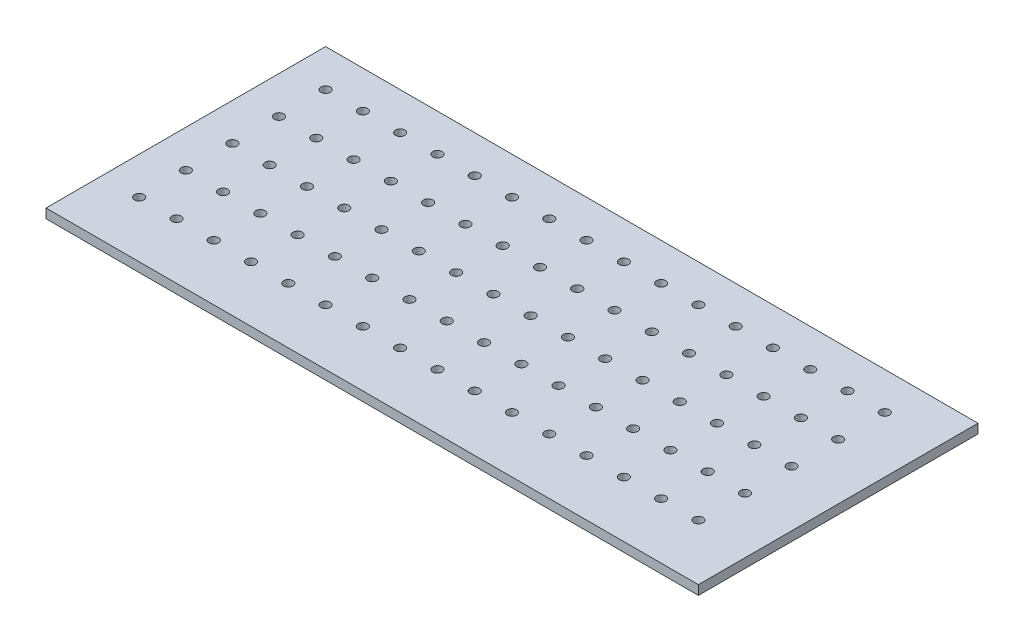
SolidWorks part; units mm, degrees
ref_plane "Alzado" through (0, 0, 0) normal (0, 0, 1) x (1, 0, 0)
ref_plane "Planta" through (0, 0, 0) normal (0, 1, 0) x (1, 0, 0)
ref_plane "Vista lateral" through (0, 0, 0) normal (1, 0, 0) x (0, 0, -1)
sketch "Croquis1" plane through (0, 0, 0) normal (0, 1, 0) x (1, 0, 0)
  line L1 (-350, -150) -> (350, -150)
  line L2 (-350, -150) -> (-350, 150)
  line L3 (-350, 150) -> (350, 150)
  line L4 (350, -150) -> (350, 150)
  line L5 (-350, -150) -> (350, 150) construction
  line L6 (-350, 150) -> (350, -150) construction
  point P0 (0, 0)
  dimension "D1" = 700
  dimension "D2" = 300
extrude "Saliente-Extruir1" add sketch "Croquis1" along normal blind 10
sketch "Croquis2" plane through (0, 10, 0) normal (0, 1, 0) x (1, 0, 0)
  line L0 (350, 150) -> (-350, 150) construction
  line L1 (-350, 150) -> (-350, -150) construction
  circle A0 centre (-310, 110) radius 5
  dimension "D1" = 40
  dimension "D2" = 40
extrude "Cortar-Extruir1" cut sketch "Croquis2" against normal blind 10
pattern_linear "MatrizL1" count 16 spacing 40 along (1, 0, 0) count 5 spacing 50 along (0, 0, 1) of "Cortar-Extruir1"
